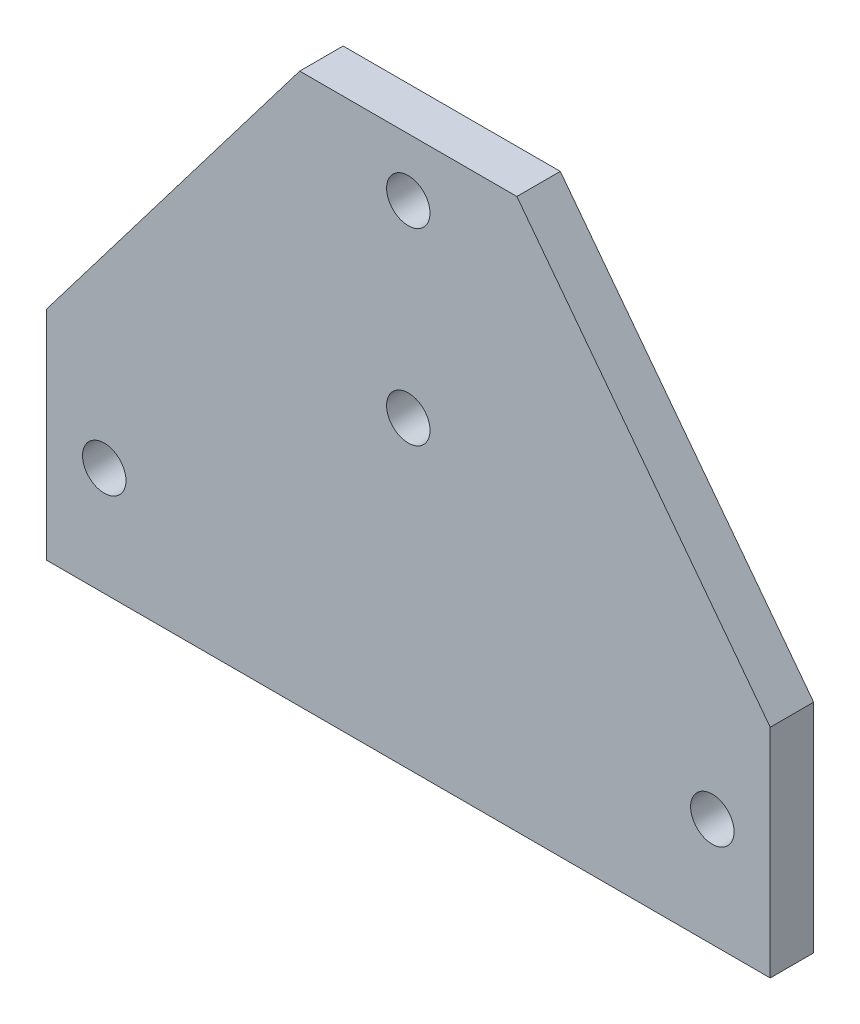
SolidWorks part; units mm, degrees
ref_plane "前视基准面" through (0, 0, 0) normal (0, 0, 1) x (1, 0, 0)
ref_plane "上视基准面" through (0, 0, 0) normal (0, 1, 0) x (1, 0, 0)
ref_plane "右视基准面" through (0, 0, 0) normal (1, 0, 0) x (0, 0, -1)
sketch "草图1" plane through (0, 0, 0) normal (0, 0, 1) x (1, 0, 0)
  line L0 (0, 0) -> (15, 0)
  line L1 (15, 0) -> (32.5, -23)
  line L2 (32.5, -23) -> (32.5, -38)
  line L3 (32.5, -38) -> (-17.5, -38)
  line L4 (-17.5, -38) -> (-17.5, -23)
  line L5 (-17.5, -23) -> (0, 0)
  point P7 (7.5, 0)
  point P8 (7.5, -38)
  dimension "D1" = 50
  dimension "D2" = 15
  dimension "D3" = 15
  dimension "D4" = 15
  dimension "D5" = 38
extrude "凸台-拉伸1" add sketch "草图1" along normal blind 3
sketch "草图2" plane through (0, 0, 3) normal (0, 0, 1) x (1, 0, 0)
  line L0 (15, 0) -> (0, 0) construction
  line L1 (32.5, -38) -> (32.5, -23) construction
  line L2 (-17.5, -38) -> (32.5, -38) construction
  circle A0 centre (7.5, -4) radius 1.5
  circle A1 centre (7.5, -17) radius 1.5
  circle A2 centre (28.5, -30.5) radius 1.5
  circle A3 centre (-13.5, -30.5) radius 1.5
  point P14 (0, 0)
  point P15 (7.5, 0)
  point P16 (0, 0)
  dimension "D6" = 3
  dimension "D1" = 4
  dimension "D2" = 13
  dimension "D3" = 4
  dimension "D4" = 42
  dimension "D5" = 7.5
extrude "切除-拉伸1" cut sketch "草图2" against normal blind 3
